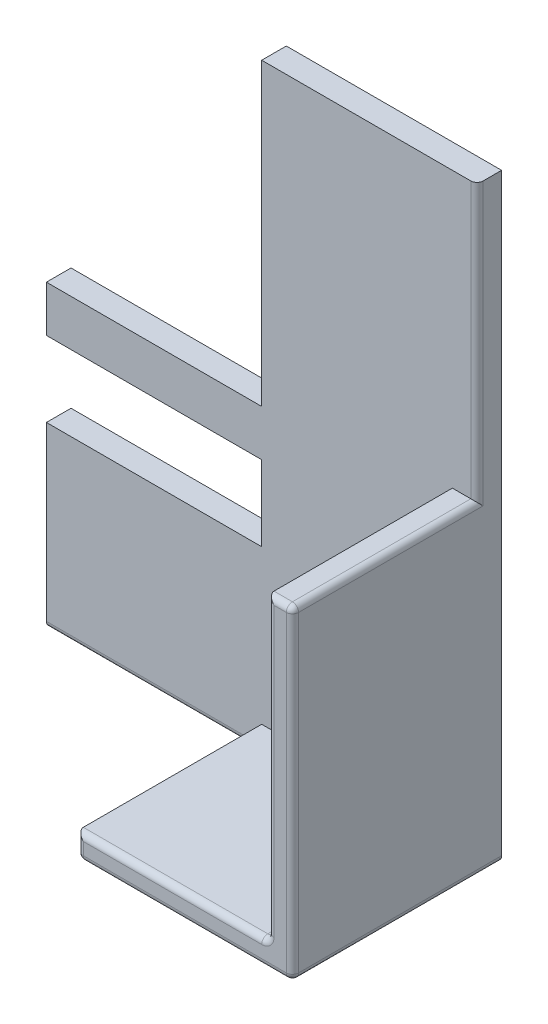
SolidWorks part; units mm, degrees
ref_plane "정면" through (0, 0, 0) normal (0, 0, 1) x (1, 0, 0)
ref_plane "윗면" through (0, 0, 0) normal (0, 1, 0) x (1, 0, 0)
ref_plane "우측면" through (0, 0, 0) normal (1, 0, 0) x (0, 0, -1)
sketch "스케치1" plane through (0, 0, 0) normal (0, 0, 1) x (1, 0, 0)
  line L1 (0, 0) -> (70, 0)
  line L2 (0, 0) -> (0, -97.5)
  line L3 (0, -97.5) -> (140, -97.5)
  line L4 (140, -19.5732) -> (140, -97.5)
  line L6 (70, 0) -> (70, 97.5)
  line L7 (70, 97.5) -> (140, 97.5)
  line L8 (140, -19.5732) -> (140, 97.5)
  dimension "D1" = 195
  dimension "D2" = 140
  dimension "D3" = 97.5
  dimension "D4" = 70
  dimension "D5" = 97.5
extrude "보스-돌출1" add sketch "스케치1" along normal blind 8
sketch "스케치2" plane through (0, 0, 0) normal (0, 0, 1) x (1, 0, 0)
  line L0 (140, -97.5) -> (140, 97.5) construction
  line L1 (127.5, 90.5) -> (129.25, 87.4689)
  line L2 (129.25, 87.4689) -> (132.75, 87.4689)
  line L3 (132.75, 87.4689) -> (134.5, 90.5)
  line L4 (134.5, 90.5) -> (132.75, 93.5311)
  line L5 (132.75, 93.5311) -> (129.25, 93.5311)
  line L6 (129.25, 93.5311) -> (127.5, 90.5)
  line L7 (129.25, -7.0311) -> (132.75, -7.0311)
  line L8 (132.75, -7.0311) -> (134.5, -4)
  line L9 (134.5, -4) -> (132.75, -0.9689)
  line L10 (132.75, -0.9689) -> (129.25, -0.9689)
  line L11 (129.25, -0.9689) -> (127.5, -4)
  line L12 (127.5, -4) -> (129.25, -7.0311)
  line L13 (136.5, -87.08) -> (134.75, -84.0489)
  line L14 (134.75, -84.0489) -> (131.25, -84.0489)
  line L15 (131.25, -84.0489) -> (129.5, -87.08)
  line L16 (129.5, -87.08) -> (131.25, -90.1111)
  line L17 (131.25, -90.1111) -> (134.75, -90.1111)
  line L18 (134.75, -90.1111) -> (136.5, -87.08)
  line L19 (83.25, -77.4689) -> (81.5, -80.5)
  line L20 (81.5, -80.5) -> (83.25, -83.5311)
  line L21 (83.25, -83.5311) -> (86.75, -83.5311)
  line L22 (86.75, -83.5311) -> (88.5, -80.5)
  line L23 (88.5, -80.5) -> (86.75, -77.4689)
  line L24 (86.75, -77.4689) -> (83.25, -77.4689)
  line L25 (83.25, -87.4689) -> (81.5, -90.5)
  line L26 (81.5, -90.5) -> (83.25, -93.5311)
  line L27 (83.25, -93.5311) -> (86.75, -93.5311)
  line L28 (86.75, -93.5311) -> (88.5, -90.5)
  line L29 (88.5, -90.5) -> (86.75, -87.4689)
  line L30 (86.75, -87.4689) -> (83.25, -87.4689)
  line L31 (140, 97.5) -> (70, 97.5) construction
  line L32 (0, -97.5) -> (140, -97.5) construction
  line L33 (37.25, -7.0018) -> (40.75, -7.0018)
  line L34 (40.75, -7.0018) -> (42.5, -3.9707)
  line L35 (42.5, -3.9707) -> (40.75, -0.9396)
  line L36 (40.75, -0.9396) -> (37.25, -0.9396)
  line L37 (37.25, -0.9396) -> (35.5, -3.9707)
  line L38 (35.5, -3.9707) -> (37.25, -7.0018)
  line L39 (70, 0) -> (0, 0) construction
  line L40 (0, 0) -> (0, -97.5) construction
  circle A0 centre (131, 90.5) radius 3.5 construction
  circle A1 centre (131, -4) radius 3.5 construction
  circle A2 centre (133, -87.08) radius 3.5 construction
  circle A3 centre (85, -80.5) radius 3.5 construction
  circle A4 centre (85, -90.5) radius 3.5 construction
  circle A5 centre (39, -3.9707) radius 3.5 construction
  dimension "D1" = 7
  dimension "D2" = 7
  dimension "D3" = 7
  dimension "D4" = 7
  dimension "D5" = 7
  dimension "D15" = 7
  dimension "D6" = 9
  dimension "D7" = 7
  dimension "D8" = 9
  dimension "D9" = 94.5
  dimension "D10" = 10.42
  dimension "D11" = 7
  dimension "D12" = 55
  dimension "D13" = 7
  dimension "D14" = 10
  dimension "D16" = 3.9707
  dimension "D17" = 39
extrude "컷-돌출1" cut sketch "스케치2" along normal blind 2
sketch "스케치3" plane through (0, 0, 2) normal (0, 0, 1) x (1, 0, 0)
  line L0 (132.75, 93.5311) -> (129.25, 93.5311) construction
  line L1 (132.75, -0.9689) -> (129.25, -0.9689) construction
  line L2 (40.75, -0.9396) -> (37.25, -0.9396) construction
  line L3 (86.75, -77.4689) -> (83.25, -77.4689) construction
  line L4 (83.25, -93.5311) -> (86.75, -93.5311) construction
  line L5 (134.75, -84.0489) -> (131.25, -84.0489) construction
  circle A0 centre (130.9896, 90.5011) radius 2
  circle A1 centre (131.0104, -3.9989) radius 2
  circle A2 centre (39.0104, -3.9696) radius 2
  circle A3 centre (85.0104, -80.4989) radius 2
  circle A4 centre (84.9896, -90.5011) radius 2
  circle A5 centre (132.9896, -87.0789) radius 2
  dimension "D1" = 4
  dimension "D4" = 4
  dimension "D7" = 4
  dimension "D10" = 4
  dimension "D11" = 4
  dimension "D16" = 4
  dimension "D2" = 3.03
  dimension "D5" = 3.03
  dimension "D6" = 3.5104
  dimension "D8" = 3.03
  dimension "D12" = 3.03
  dimension "D13" = 3.03
  dimension "D15" = 3.5104
  dimension "D17" = 3.03
extrude "컷-돌출2" cut sketch "스케치3" along normal blind 5
sketch "스케치4" plane through (0, 0, 8) normal (0, 0, 1) x (1, 0, 0)
  line L1 (140, -97.5) -> (70, -97.5)
  line L2 (140, -97.5) -> (140, -89.5)
  line L3 (140, -89.5) -> (70, -89.5)
  line L4 (70, -97.5) -> (70, -89.5)
  line L5 (140, -89.5) -> (132, -89.5)
  line L6 (140, -89.5) -> (140, 8)
  line L7 (140, 8) -> (132, 8)
  line L8 (132, -89.5) -> (132, 8)
  line M8 (0, -97.5) -> (140, -97.5)
  line M9 (140, -97.5) -> (140, 97.5)
  dimension "D1" = 8
  dimension "D2" = 8
  dimension "D3" = 70
  dimension "D4" = 97.5
extrude "보스-돌출2" add sketch "스케치4" along normal blind 60 contours L8 L3 L7 M9 | L4 L3 M8 M9
fillet "필렛1" radius 2 12 edges at (132, -40.75, 68) (136, 8, 68) (70, -93.5, 68) (140, -44.75, 68) (101, -89.5, 68) (105, -97.5, 68) (132, -89.5, 38) (140, 52.75, 8) (140, 8, 38) (35, -97.5, 8) (70, -97.5, 38) (140, -97.5, 34)
sketch "스케치5" plane through (0, 0, 8) normal (0, 0, 1) x (1, 0, 0)
  line L1 (0, 0) -> (70, 0)
  line L2 (0, 0) -> (0, -15)
  line L3 (0, -15) -> (70, -15)
  line L4 (70, 0) -> (70, -15)
  line L5 (0, -15) -> (70, -15)
  line L6 (0, -15) -> (0, -39.5)
  line L7 (0, -39.5) -> (70, -39.5)
  line L8 (70, -15) -> (70, -39.5)
  line L9 (72, -97.5) -> (0, -97.5) construction
  line M17 (0, 0) -> (0, -95.5)
  dimension "D1" = 58
  dimension "D2" = 15
extrude "컷-돌출4" cut sketch "스케치5" against normal blind 20 contours L8 L3 L7 M17
